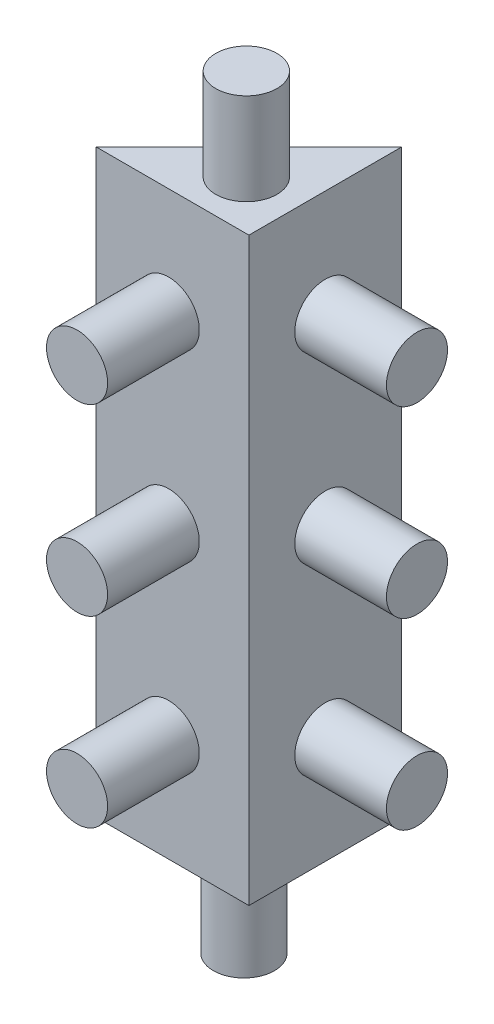
SolidWorks part; units mm, degrees
ref_plane "Front Plane" through (0, 0, 0) normal (0, 0, 1) x (1, 0, 0)
ref_plane "Top Plane" through (0, 0, 0) normal (0, 1, 0) x (1, 0, 0)
ref_plane "Right Plane" through (0, 0, 0) normal (1, 0, 0) x (0, 0, -1)
sketch "Sketch4" plane through (0, 0, 0) normal (0, 1, 0) x (1, 0, 0)
  line L0 (-6.0356, -6.0356) -> (6.6644, 6.6644)
  line L3 (-6.0356, -6.0356) -> (6.6644, -6.0356)
  line L4 (6.6644, 6.6644) -> (6.6644, -6.0356)
  line L5 (0, 0) -> (6.6644, -6.0356) construction
  line L6 (-6.0356, -6.0356) -> (6.6644, 6.6644) construction
  point P0 (0, 0)
  dimension "D1" = 12.7
  dimension "D2" = 12.7
extrude "Boss-Extrude1" add sketch "Sketch4" along normal blind 48.26
sketch "Sketch6" plane through (0, 0, 6.0356) normal (0, 0, 1) x (1, 0, 0)
  line L0 (-6.0356, 0) -> (6.6644, 0) construction
  circle A0 centre (0, 8.89) radius 2.54
  circle A1 centre (0, 24.13) radius 2.54
  circle A2 centre (0, 39.37) radius 2.54
  dimension "D1" = 5.08
  dimension "D2" = 15.24
  dimension "D3" = 15.24
  dimension "D4" = 8.89
extrude "Boss-Extrude3" add sketch "Sketch6" along normal blind 7.62
sketch "Sketch7" plane through (6.6644, 0, 0) normal (1, 0, 0) x (0, 0, -1)
  line L0 (-6.0356, 0) -> (6.6644, 0) construction
  circle A0 centre (0.3144, 8.89) radius 2.54
  circle A1 centre (0.3144, 24.13) radius 2.54
  circle A2 centre (0.3144, 39.37) radius 2.54
  dimension "D1" = 5.08
  dimension "D2" = 15.24
  dimension "D3" = 15.24
  dimension "D4" = 8.89
extrude "Boss-Extrude4" add sketch "Sketch7" along normal blind 7.62
sketch "Sketch8" plane through (0, 0, 0) normal (0, -1, 0) x (1, 0, 0)
  circle A0 centre (2.2592, 2.046) radius 2.54
  dimension "D1" = 5.08
  dimension "D2" = 3.048
extrude "Boss-Extrude5" add sketch "Sketch8" along normal blind 7.62
sketch "Sketch9" plane through (0, 48.26, 0) normal (0, 1, 0) x (1, 0, 0)
  line L0 (6.6644, 6.6644) -> (-6.0356, -6.0356) construction
  circle A0 centre (2.3604, -1.9448) radius 2.54
  point P6 (0.3144, 0.3144)
  dimension "D1" = 5.08
  dimension "D2" = 3.048
extrude "Boss-Extrude6" add sketch "Sketch9" along normal blind 7.62
sketch "Sketch10" plane through (0, -7.62, 0) normal (0, -1, 0) x (1, 0, 0)
  circle A0 centre (2.2592, 2.046) radius 2.54 construction
  circle A1 centre (2.2592, 2.046) radius 2.54
sketch "Sketch11" plane through (14.2844, 0, 0) normal (1, 0, 0) x (0, 0, -1)
  circle A0 centre (0.3144, 8.89) radius 2.54 construction
  circle A1 centre (0.3144, 24.13) radius 2.54 construction
  circle A2 centre (0.3144, 39.37) radius 2.54 construction
  circle A3 centre (0.3144, 8.89) radius 2.54
  circle A4 centre (0.3144, 24.13) radius 2.54
  circle A5 centre (0.3144, 39.37) radius 2.54
  point P9 (0, 0)
